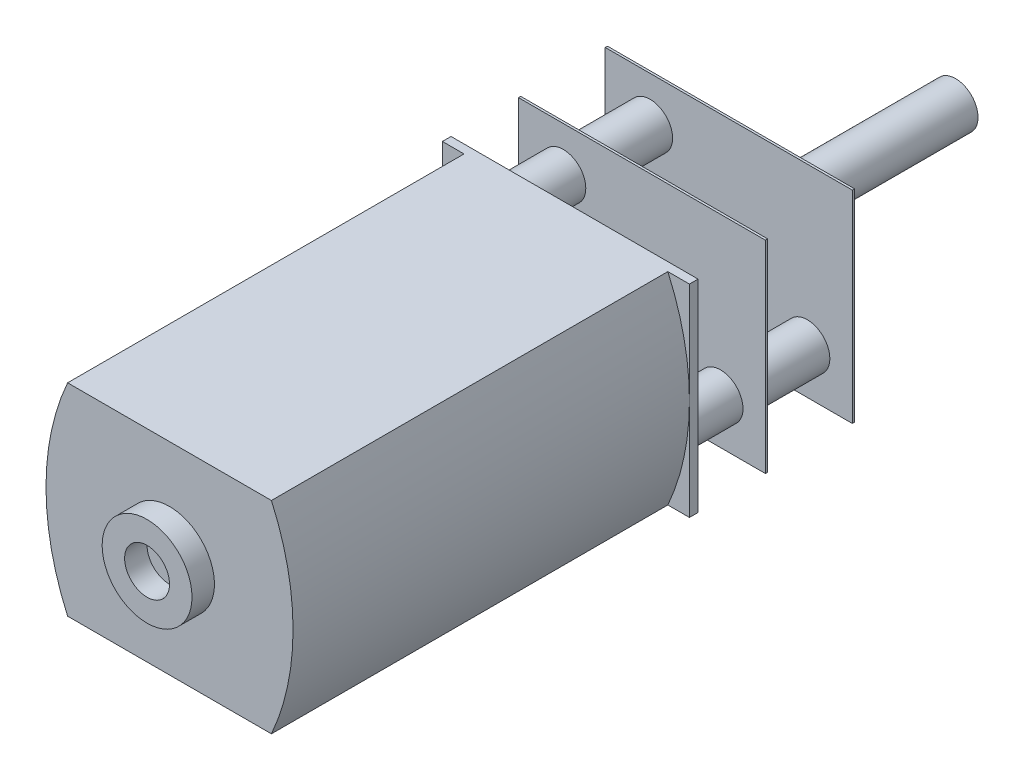
SolidWorks part; units mm, degrees
ref_plane "Front" through (0, 0, 0) normal (0, 0, 1) x (1, 0, 0)
ref_plane "Top" through (0, 0, 0) normal (0, 1, 0) x (1, 0, 0)
ref_plane "Right" through (0, 0, 0) normal (1, 0, 0) x (0, 0, -1)
sketch "Sketch1" plane through (0, 0, 0) normal (0, 1, 0) x (1, 0, 0)
  line L1 (0, 0) -> (11, 0)
  line L2 (0, 0) -> (0, 25)
  line L3 (0, 25) -> (11, 25)
  line L4 (11, 0) -> (11, 25)
extrude "Boss-Extrude1" add sketch "Sketch1" along normal blind 9
sketch "Sketch2" plane through (0, 9, 0) normal (0, 1, 0) x (1, 0, 0)
  line L0 (0, 24.9) -> (0, 21.1343)
  line L1 (11, 0) -> (11, 25) construction
  line L2 (11, 24.9) -> (0, 24.9)
  line L3 (0, 25) -> (0, 0) construction
  line L4 (0, 21.0343) -> (11, 21.0343)
  line L5 (11, 24.9) -> (11, 21.1343)
  line L6 (0, 21.0343) -> (0, 18.0343)
  line L7 (0, 21.1343) -> (11, 21.1343)
  line L8 (0, 18.0343) -> (11, 18.0343)
  line L9 (11, 18.0343) -> (11, 21.0343)
  line M1 (0, 25) -> (0, 0)
  line M3 (11, 0) -> (11, 25)
extrude "Cut-Extrude2" cut sketch "Sketch2" against normal through all contours L8 L4 M1 M3 | L7 L2 M1 M3
sketch "Sketch3" plane through (0, 0, 0) normal (0, 0, 1) x (1, 0, 0)
  line L0 (11, 0) -> (11, 9) construction
  line L1 (0.9626, 9) -> (10.0374, 9)
  line L2 (0, 9) -> (11, 9) construction
  line L3 (0.9626, 0) -> (10.0374, 0)
  line L4 (0, 0) -> (11, 0) construction
  arc A0 (0.9626, 9) -> (0.9626, 0) centre (11, 4.5) ccw
  arc A1 (10.0374, 0) -> (10.0374, 9) centre (0, 4.5) ccw
  line M5 (0, 0) -> (11, 0)
  line M6 (11, 0) -> (11, 9)
  line M7 (11, 9) -> (0, 9)
  line M8 (0, 9) -> (0, 0)
extrude "Cut-Extrude3" cut sketch "Sketch3" against normal blind 17.65 contours A1 M6 M7 | A1 M5 M6 | A0 M8 M5 | A0 M7 M8
sketch "Sketch4" plane through (0, 0, -25) normal (0, 0, -1) x (-1, 0, 0)
  circle A0 centre (-2, 7) radius 1
  circle A1 centre (-9, 2) radius 1
extrude "Boss-Extrude2" add sketch "Sketch4" against normal up to surface (6.9657 mm away)
sketch "Sketch5" plane through (0, 0, 0) normal (0, 0, 1) x (1, 0, 0)
  circle A0 centre (5.5, 4.5) radius 2
  circle A1 centre (5.5, 4.5) radius 1
extrude "Boss-Extrude3" add sketch "Sketch5" along normal blind 1
sketch "Sketch6" plane through (0, 0, -25) normal (0, 0, -1) x (-1, 0, 0)
  circle A0 centre (-5.5, 4.5) radius 1
extrude "Boss-Extrude4" add sketch "Sketch6" along normal blind 10
